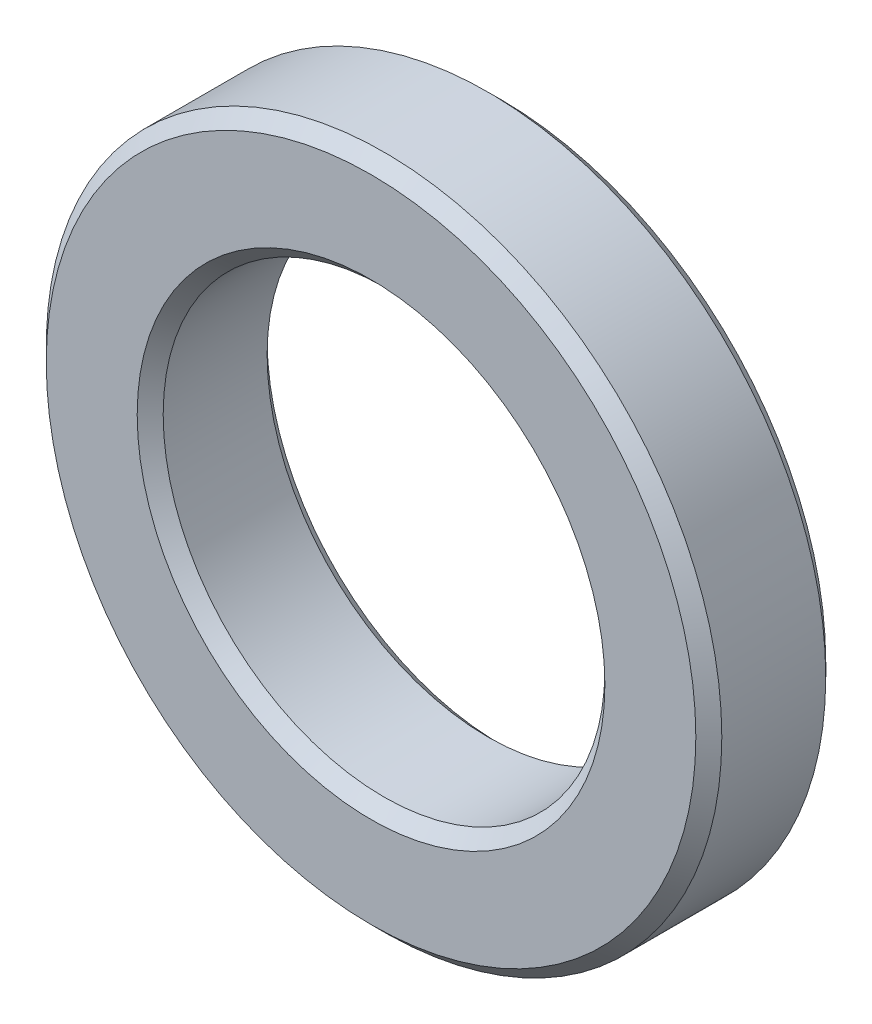
SolidWorks part; units mm, degrees
ref_plane "前视基准面" through (0, 0, 0) normal (0, 0, 1) x (1, 0, 0)
ref_plane "上视基准面" through (0, 0, 0) normal (0, 1, 0) x (1, 0, 0)
ref_plane "右视基准面" through (0, 0, 0) normal (1, 0, 0) x (0, 0, -1)
sketch "草图1" plane through (0, 0, 0) normal (0, 0, 1) x (1, 0, 0)
  circle A0 centre (0, 0) radius 8.5
  circle A1 centre (0, 0) radius 13
  dimension "D1" = 17
  dimension "D2" = 26
extrude "凸台-拉伸1" add sketch "草图1" along normal blind 5
chamfer "倒角1" distance 0.5 angle 45 4 edges at (8.5, 0, 0) (13, 0, 0) (8.5, 0, 5) (13, 0, 5)
